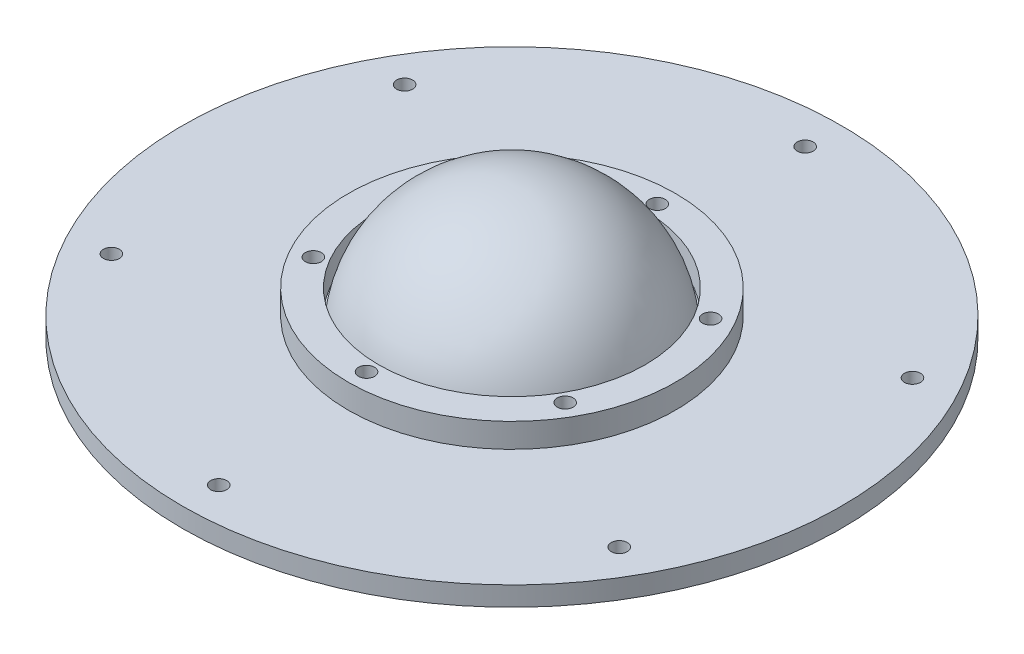
SolidWorks part; units mm, degrees
ref_plane "Front" through (0, 0, 0) normal (0, 0, 1) x (1, 0, 0)
ref_plane "Top" through (0, 0, 0) normal (0, 1, 0) x (1, 0, 0)
ref_plane "Right" through (0, 0, 0) normal (1, 0, 0) x (0, 0, -1)
sketch "Sketch1" plane through (0, 0, 0) normal (0, 0, 1) x (1, 0, 0)
  line L2 (-65, 0) -> (-65, 5)
  line L3 (-65, 5) -> (-54.7723, 5)
  line L8 (0, 0) -> (0, 55) construction
  line L9 (0, 55) -> (0, 50)
  line L10 (-65, 0) -> (55, 0) construction
  line L11 (-65, 0) -> (-50, 0)
  arc A0 (55, 0) -> (-55, 0) centre (0, 0) ccw construction
  arc A1 (0, 50) -> (-50, 0) centre (0, 0) ccw
  arc A2 (-54.7723, 5) -> (0, 55) centre (0, 0) cw
  dimension "D1" = 110
  dimension "D2" = 100
  dimension "D3" = 10
  dimension "D6" = 5
revolve "Revolve1" add sketch "Sketch1" angle 360 about L8
sketch "Sketch2" plane through (0, 0, 0) normal (0, 1, 0) x (1, 0, 0)
  circle A0 centre (0, 0) radius 136
  dimension "D1" = 272
  dimension "D2" = 0
extrude "Boss-Extrude1" add sketch "Sketch2" along normal blind 8
sketch "Sketch3" plane through (0, 0, 0) normal (0, 1, 0) x (1, 0, 0)
  circle A0 centre (0, 0) radius 108.5
  circle A1 centre (0, 0) radius 111.5
  dimension "D1" = 217
  dimension "D2" = 223
extrude "Cut-Extrude1" cut sketch "Sketch3" along normal blind 2 contours A0 | A1
sketch "Sketch4" plane through (0, 0, 0) normal (0, -1, 0) x (-1, 0, 0)
  line L1 (0, 136) -> (0, 121) construction
  circle A0 centre (0, 0) radius 136 construction
  circle A1 centre (0, 121) radius 3.3
  dimension "D2" = 6.6
  dimension "D1" = 15
extrude "Cut-Extrude2" cut sketch "Sketch4" against normal blind 22
pattern_circular "CirPattern1" count 6 over 360 about axis through (0, 0, 0) along (0, 1, 0) of "Cut-Extrude2"
sketch "Sketch6" plane through (0, 8, 0) normal (0, 1, 0) x (1, 0, 0)
  circle A0 centre (0, 0) radius 55
  circle A1 centre (0, 0) radius 67.5
  dimension "D1" = 110
  dimension "D2" = 135
extrude "Boss-Extrude2" add sketch "Sketch6" along normal blind 10 contours A1 | A0
sketch "Sketch7" plane through (0, 18, 0) normal (0, 1, 0) x (1, 0, 0)
  line L0 (0, 0) -> (0, -60) construction
  circle A0 centre (0, -60) radius 3.3
  dimension "D1" = 6.6
  dimension "D2" = 60
extrude "Cut-Extrude3" cut sketch "Sketch7" against normal blind 15 contours A0
pattern_circular "CirPattern2" count 6 over 360 about axis through (0, 0, 0) along (0, 1, 0) of "Cut-Extrude3"
